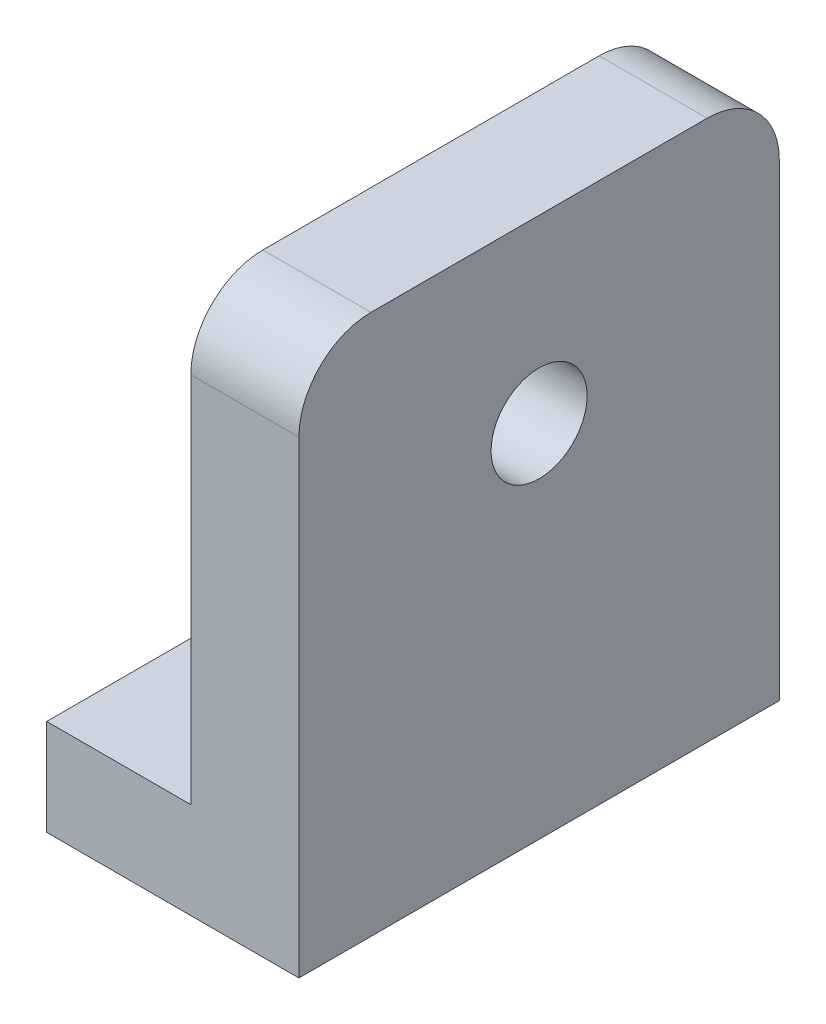
SolidWorks part; units mm, degrees
ref_plane "前视基准面" through (0, 0, 0) normal (0, 0, 1) x (1, 0, 0)
ref_plane "上视基准面" through (0, 0, 0) normal (0, 1, 0) x (1, 0, 0)
ref_plane "右视基准面" through (0, 0, 0) normal (1, 0, 0) x (0, 0, -1)
sketch "草图1" plane through (0, 0, 0) normal (0, 0, 1) x (1, 0, 0)
  line L0 (0, 0) -> (-21, 0)
  line L1 (-21, 0) -> (-21, 8)
  line L2 (-21, 8) -> (-9, 8)
  line L3 (0, 0) -> (0, 45)
  line L4 (0, 45) -> (-9, 45)
  line L5 (-9, 45) -> (-9, 8)
  dimension "D1" = 21
  dimension "D2" = 8
  dimension "D3" = 12
  dimension "D4" = 45
extrude "凸台-拉伸1" add sketch "草图1" along normal blind 40
fillet "圆角1" radius 6 2 edges at (-4.5, 45, 0) (-4.5, 45, 40)
sketch "草图2" plane through (-9, 0, 0) normal (-1, 0, 0) x (0, 0, 1)
  line L0 (34, 45) -> (6, 45) construction
  circle A0 centre (20, 30) radius 4
  dimension "D1" = 8
  dimension "D2" = 15
extrude "切除-拉伸1" cut sketch "草图2" against normal through all
